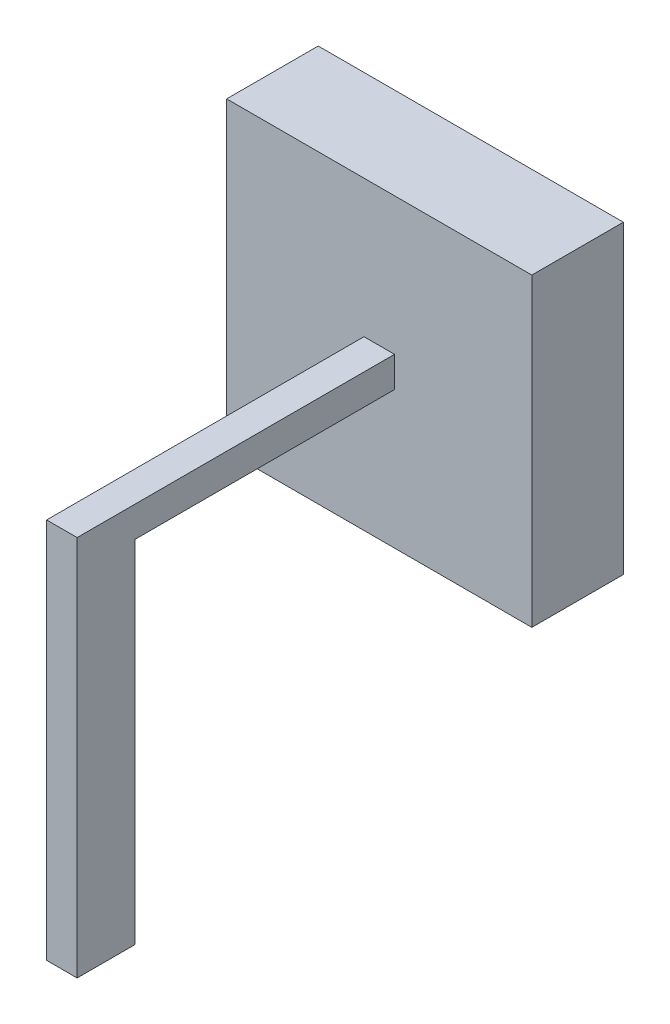
SolidWorks part; units mm, degrees
ref_plane "Front Plane" through (0, 0, 0) normal (0, 0, 1) x (1, 0, 0)
ref_plane "Top Plane" through (0, 0, 0) normal (0, 1, 0) x (1, 0, 0)
ref_plane "Right Plane" through (0, 0, 0) normal (1, 0, 0) x (0, 0, -1)
sketch "Sketch1" plane through (0, 0, 0) normal (0, 0, 1) x (1, 0, 0)
  line L1 (5, -5) -> (-5, -5)
  line L2 (5, -5) -> (5, 5)
  line L3 (5, 5) -> (-5, 5)
  line L4 (-5, -5) -> (-5, 5)
  line L5 (5, -5) -> (-5, 5) construction
  line L6 (5, 5) -> (-5, -5) construction
  point P0 (0, 0)
  dimension "D1" = 10
  dimension "D2" = 10
extrude "Boss-Extrude3" add sketch "Sketch1" against normal blind 3
sketch "Sketch5" plane through (0, 0, 0) normal (0, 0, 1) x (1, 0, 0)
  line L1 (0.5, -0.5) -> (-0.5, -0.5)
  line L2 (0.5, -0.5) -> (0.5, 0.5)
  line L3 (0.5, 0.5) -> (-0.5, 0.5)
  line L4 (-0.5, -0.5) -> (-0.5, 0.5)
  line L5 (0.5, -0.5) -> (-0.5, 0.5) construction
  line L6 (0.5, 0.5) -> (-0.5, -0.5) construction
  point P0 (0, 0)
  dimension "D1" = 1
  dimension "D2" = 1
extrude "Boss-Extrude4" add sketch "Sketch5" along normal blind 10.4
sketch "Sketch6" plane through (0, 0.5, 0) normal (0, 1, 0) x (1, 0, 0)
  line L0 (-0.5, -10.4) -> (-0.5, 0) construction
  line L1 (0.5, -10.4) -> (-0.5, -10.4)
  line L2 (0.5, -10.4) -> (0.5, -8.5)
  line L3 (0.5, -8.5) -> (-0.5, -8.5)
  line L4 (-0.5, -10.4) -> (-0.5, -8.5)
  dimension "D1" = 1.9
extrude "Boss-Extrude5" add sketch "Sketch6" against normal blind 12.5
